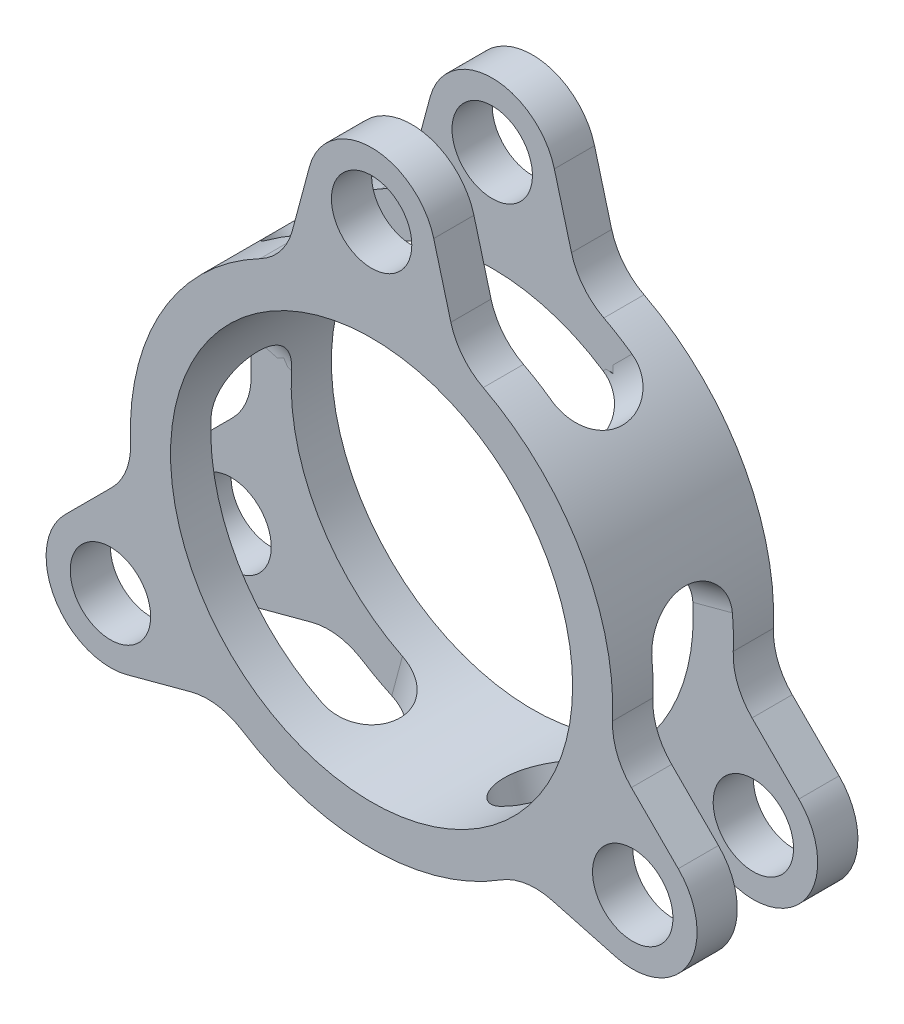
SolidWorks part; units mm, degrees
ref_plane "Front Plane" through (0, 0, 0) normal (0, 0, 1) x (1, 0, 0)
ref_plane "Top Plane" through (0, 0, 0) normal (0, 1, 0) x (1, 0, 0)
ref_plane "Right Plane" through (0, 0, 0) normal (1, 0, 0) x (0, 0, -1)
sketch "Sketch1" plane through (0, 0, 0) normal (0, 0, 1) x (1, 0, 0)
  line L0 (0, 0) -> (0, 60.082) construction
  line L1 (-7.7274, 39.5706) -> (-9.8591, 31.615)
  line L2 (7.7274, 39.5706) -> (9.8591, 31.615)
  line L3 (38.1328, -13.0931) -> (32.3089, -7.2693)
  line L4 (30.4054, -26.4774) -> (22.4498, -24.3457)
  line L5 (-30.4054, -26.4774) -> (-22.4498, -24.3457)
  line L6 (-38.1328, -13.0931) -> (-32.3089, -7.2693)
  arc A0 (4.9889, 37.1667) -> (-7.9544, 36.6467) centre (0, 0) ccw construction
  arc A1 (-13.8841, 26.5938) -> (-29.973, -1.273) centre (0, 0) ccw
  circle A2 centre (0, 0) radius 25
  circle A3 centre (0, 37.5) radius 5
  arc A15 (-16.0889, -25.3209) -> (16.0889, -25.3209) centre (0, 0) ccw
  arc A16 (29.973, -1.273) -> (13.8841, 26.5938) centre (0, 0) ccw
  arc A17 (-13.8841, 26.5938) -> (-9.8591, 31.615) centre (-17.5865, 33.6855) ccw
  arc A18 (13.8841, 26.5938) -> (9.8591, 31.615) centre (17.5865, 33.6855) cw
  arc A19 (7.7274, 39.5706) -> (-7.7274, 39.5706) centre (0, 37.5) ccw
  arc A20 (30.4054, -26.4774) -> (38.1328, -13.0931) centre (32.476, -18.75) ccw
  arc A21 (-8.5467, 36.5131) -> (-35.7141, -11.4347) centre (0, 0) ccw construction
  arc A22 (16.0889, -25.3209) -> (22.4498, -24.3457) centre (20.3793, -32.0731) cw
  circle A23 centre (32.476, -18.75) radius 5
  arc A24 (29.973, -1.273) -> (32.3089, -7.2693) centre (37.9658, -1.6124) ccw
  arc A25 (-38.1328, -13.0931) -> (-30.4054, -26.4774) centre (-32.476, -18.75) ccw
  arc A26 (-29.973, -1.273) -> (-32.3089, -7.2693) centre (-37.9658, -1.6124) cw
  circle A27 centre (-32.476, -18.75) radius 5
  arc A28 (-16.0889, -25.3209) -> (-22.4498, -24.3457) centre (-20.3793, -32.0731) ccw
  point P31 (0, 0)
  point P46 (0, 0)
  dimension "D1" = 50
  dimension "D2" = 60
  dimension "D3" = 75
  dimension "D4" = 10
  dimension "D5" = 3
  dimension "D8" = 8
  dimension "D7" = 15
extrude "Boss-Extrude1" add sketch "Sketch1" along normal blind 20
sketch "Sketch9" plane through (0, 0, 0) normal (0, 0, -1) x (-1, 0, 0)
  line L0 (0, 0) -> (0, 45.5)
  line L1 (0, 0) -> (21.2132, 21.2132)
  line L2 (0, 0) -> (-21.2132, 21.2132)
  line L3 (-21.2132, 21.2132) -> (21.2132, 21.2132)
  arc A0 (7.7274, 39.5706) -> (-7.7274, 39.5706) centre (0, 37.5) ccw construction
  arc A1 (29.973, -1.273) -> (13.8841, 26.5938) centre (0, 0) ccw construction
  arc A2 (-13.8841, 26.5938) -> (-29.973, -1.273) centre (0, 0) ccw construction
  dimension "D1" = 45
  dimension "D2" = 45
ref_plane "Plane3" through (0, 0, 0) normal (-0.7071, -0.7071, 0) x (-0.7071, 0.7071, 0)
sketch "Sketch14" plane through (0, 0, 0) normal (-0.7071, -0.7071, 0) x (-0.7071, 0.7071, 0)
  line L0 (19.1115, -10) -> (5, -10) construction
  line L3 (19.1115, -15) -> (5, -15)
  line L4 (19.1115, -5) -> (5, -5)
  line L5 (0, 0) -> (0, -26.8098)
  arc A0 (19.1115, -15) -> (19.1115, -5) centre (19.1115, -10) ccw
  arc A1 (5, -5) -> (5, -15) centre (5, -10) ccw
  point P4 (0, -10)
  point P5 (0, 0)
  point P6 (12.0558, -10)
  dimension "D1" = 5
extrude "Cut-Extrude2" cut sketch "Sketch14" against normal through all
ref_plane "Plane4" through (0, 0, 0) normal (-0.7071, 0.7071, 0) x (0.7071, 0.7071, 0)
sketch "Sketch15" plane through (0, 0, 0) normal (-0.7071, 0.7071, 0) x (0.7071, 0.7071, 0)
  line L0 (0, 0) -> (0, -20) construction
  line L4 (-22.0942, -20) -> (8.9872, -20) construction
  line L5 (17.5514, -10) -> (5, -10) construction
  line L6 (17.5514, -15) -> (5, -15)
  line L7 (17.5514, -5) -> (5, -5)
  arc A2 (17.5514, -15) -> (17.5514, -5) centre (17.5514, -10) ccw
  arc A3 (5, -5) -> (5, -15) centre (5, -10) ccw
  point P11 (11.2757, -10)
  point P16 (0, -10)
  point P17 (0, -10)
  dimension "D1" = 5
extrude "Cut-Extrude5" cut sketch "Sketch15" along normal through all
sketch "Sketch16" plane through (0, 0, 0) normal (-0.7071, 0.7071, 0) x (0.7071, 0.7071, 0)
  line L0 (14.7474, -5) -> (39.8372, -5)
  line L1 (5, -5) -> (24.4949, -5) construction
  line L2 (14.7474, -15) -> (39.8372, -15)
  line L3 (24.4949, -15) -> (5, -15) construction
  line L4 (39.8372, -15) -> (39.8372, -5)
  line L5 (14.7474, -5) -> (14.7474, -15)
ref_plane "Plane5" through (0, 21.2132, 0) normal (0, -1, 0) x (-1, 0, 0)
sketch "Sketch17" plane through (0, 21.2132, 0) normal (0, -1, 0) x (-1, 0, 0)
  line L0 (12.4489, -5) -> (-15.0486, -5)
  line L1 (-15.0486, -5) -> (-15.0486, -15)
  line L2 (-15.0486, -15) -> (12.4489, -15)
  line L3 (12.4489, -15) -> (12.4489, -5)
  line L4 (7.7274, 0) -> (-7.7274, 0) construction
  line L5 (-7.7274, -20) -> (7.7274, -20) construction
  dimension "D1" = 5
  dimension "D2" = 5
extrude "Cut-Extrude7" cut sketch "Sketch17" against normal through all
pattern_circular "CirPattern1" count 3 over 360 about axis through (0, 0, 0) along (0, 0, 1) of "Cut-Extrude2", "Cut-Extrude5", "Cut-Extrude7"
